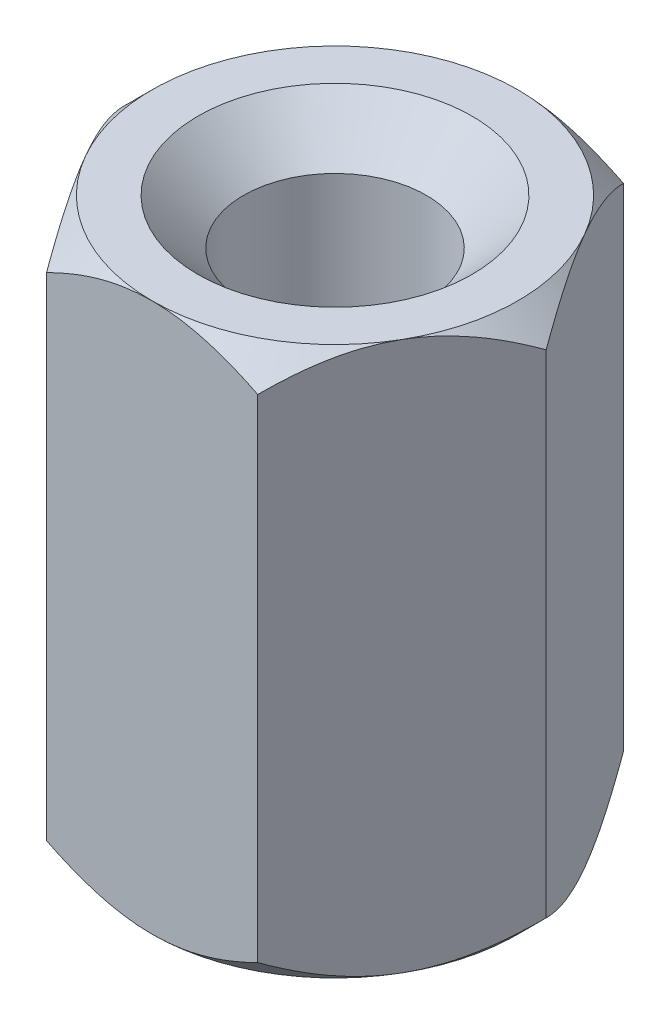
SolidWorks part; units mm, degrees
material "황동"
ref_plane "정면" through (0, 0, 0) normal (0, 0, 1) x (1, 0, 0)
ref_plane "윗면" through (0, 0, 0) normal (0, 1, 0) x (1, 0, 0)
ref_plane "우측면" through (0, 0, 0) normal (1, 0, 0) x (0, 0, -1)
sketch "Sketch1" plane through (0, 0, 0) normal (0, 1, 0) x (1, 0, 0)
  line L1 (1.1547, 2) -> (-1.1547, 2)
  line L2 (-1.1547, 2) -> (-2.3094, 0)
  line L3 (-2.3094, 0) -> (-1.1547, -2)
  line L4 (-1.1547, -2) -> (1.1547, -2)
  line L5 (1.1547, -2) -> (2.3094, 0)
  line L6 (2.3094, 0) -> (1.1547, 2)
  circle A0 centre (0, 0) radius 2 construction
  dimension "D" = 4
extrude "Extrude1" add sketch "Sketch1" along normal blind 6
sketch "Sketch3" plane through (0, 0, 0) normal (1, 0, 0) x (0, 0, -1)
  line L0 (1.5, 6) -> (1, 5.5)
  line L1 (0, 6) -> (1.5, 6)
  line L2 (0, 6) -> (0, 0)
  line L3 (0, 0) -> (1.5, 0)
  line L4 (1, 5.5) -> (1, 0.5)
  line L5 (0, 6) -> (2, 6) construction
  line L6 (1, 0.5) -> (1.5, 0)
  line L7 (0, 0) -> (2, 0) construction
  dimension "D1" = 45
  dimension "D2" = 0.5
  dimension "M" = 2
  dimension "D3" = 45
revolve "Cut-Revolve1" cut sketch "Sketch3" angle 360 about L2
sketch "Sketch4" plane through (0, 0, 0) normal (1, 0, 0) x (0, 0, -1)
  line L0 (2, 6) -> (4.5, 6)
  line L1 (4.5, 6) -> (4.5, 3.5)
  line L2 (4.5, 3.5) -> (2, 6)
  line L3 (2, 0) -> (4.5, 0)
  line L4 (4.5, 0) -> (4.5, 2.5)
  line L5 (4.5, 2.5) -> (2, 0)
  line L6 (1.5, 6) -> (-1.5, 6) construction
  line L7 (0, 0) -> (0, 6) construction
  dimension "D3" = 1
  dimension "D1" = 2
revolve "Cut-Revolve3" cut sketch "Sketch4" angle 360 about L7
equation "\"Mass\"= \"SW-질량\" / 1000"
equation "\"D1@Sketch4\"= 0.5 * \"D@Sketch1\""
